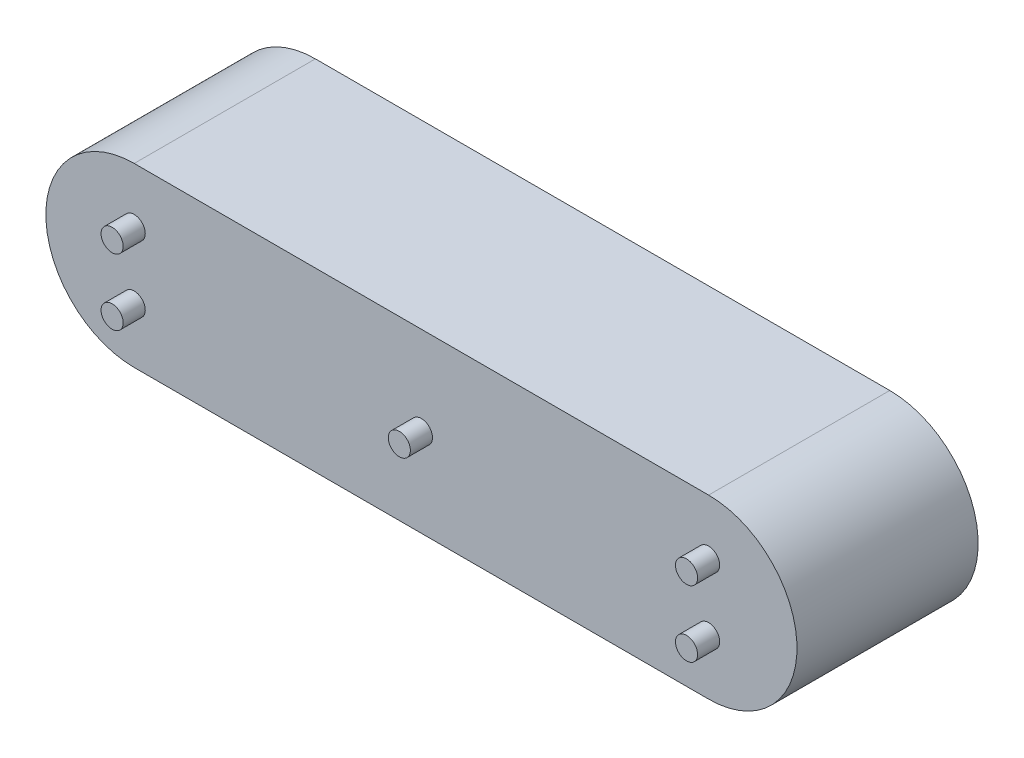
SolidWorks part; units mm, degrees
material "Custom Plastic"
ref_plane "Front Plane" through (0, 0, 0) normal (0, 0, 1) x (1, 0, 0)
ref_plane "Top Plane" through (0, 0, 0) normal (0, 1, 0) x (1, 0, 0)
ref_plane "Right Plane" through (0, 0, 0) normal (1, 0, 0) x (0, 0, -1)
sketch "Sketch1" plane through (0, 0, 0) normal (0, 0, 1) x (1, 0, 0)
  line L0 (0, 0) -> (-130, 15) construction
  line L1 (0, 0) -> (-130, 0) construction
  line L2 (0, 0) -> (0, 15) construction
  line L3 (0, 15) -> (-130, 15) construction
  line L4 (-130, 0) -> (-130, 15) construction
  circle A0 centre (0, 0) radius 2.5
  circle A1 centre (0, 15) radius 2.5
  circle A2 centre (-130, 15) radius 2.5
  circle A3 centre (-130, 0) radius 2.5
  circle A4 centre (-65, 7.5) radius 2.5
  dimension "D1" = 5
  dimension "D2" = 130
  dimension "D3" = 15
extrude "Boss-Extrude1" add sketch "Sketch1" along normal blind 5 and the other way blind 46
sketch "Sketch2" plane through (0, 0, 0) normal (0, 0, 1) x (1, 0, 0)
  line L0 (-130, 7.5) -> (0, 7.5) construction
  line L1 (-130, 27.5) -> (0, 27.5)
  line L2 (-130, -12.5) -> (0, -12.5)
  line L3 (-65, 7.5) -> (0, 0) construction
  arc A0 (-130, 27.5) -> (-130, -12.5) centre (-130, 7.5) ccw
  arc A1 (0, -12.5) -> (0, 27.5) centre (0, 7.5) ccw
  point P2 (-65, 7.5)
  dimension "D1" = 40
extrude "Boss-Extrude2" add sketch "Sketch2" against normal blind 41
